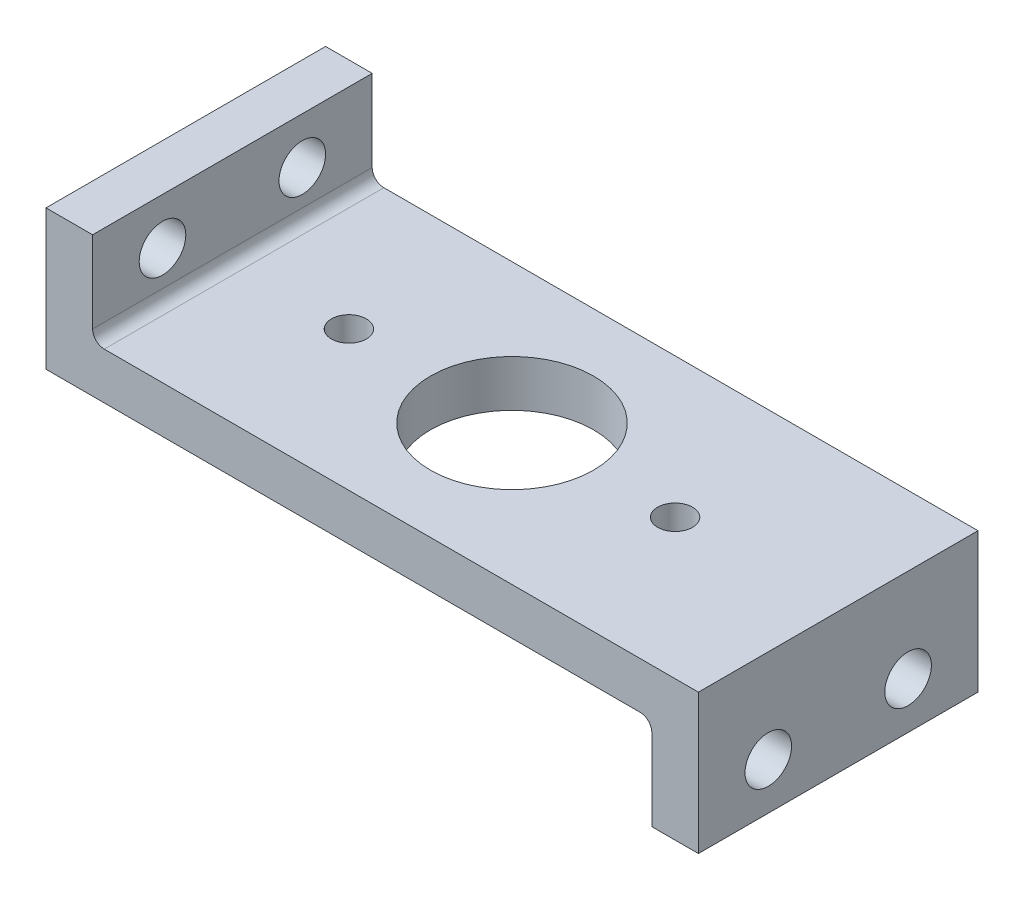
SolidWorks part; units mm, degrees
material "Alloy Steel"
ref_plane "Front Plane" through (0, 0, 0) normal (0, 0, 1) x (1, 0, 0)
ref_plane "Top Plane" through (0, 0, 0) normal (0, 1, 0) x (1, 0, 0)
ref_plane "Right Plane" through (0, 0, 0) normal (1, 0, 0) x (0, 0, -1)
sketch "Sketch1" plane through (0, 0, 0) normal (0, 1, 0) x (1, 0, 0)
  line L1 (-88.9, 38.1) -> (88.9, 38.1)
  line L2 (-88.9, 38.1) -> (-88.9, -38.1)
  line L3 (-88.9, -38.1) -> (88.9, -38.1)
  line L4 (88.9, 38.1) -> (88.9, -38.1)
  circle A0 centre (0, 0) radius 22.225
  circle A1 centre (-44.45, 0) radius 4.7625
  circle A2 centre (44.45, 0) radius 4.7625
  point P4 (0, -38.1)
  point P6 (-88.9, 0)
  dimension "D3" = 44.45
  dimension "D4" = 9.525
  dimension "D5" = 9.525
  dimension "D1" = 177.8
  dimension "D2" = 76.2
  dimension "D6" = 44.45
  dimension "D7" = 88.9
extrude "Boss-Extrude1" add sketch "Sketch1" along normal blind 12.7
sketch "Sketch2" plane through (0, 12.7, 0) normal (0, 1, 0) x (1, 0, 0)
  line L0 (-88.9, -38.1) -> (88.9, -38.1) construction
  line L1 (-88.9, 38.1) -> (-76.2, 38.1)
  line L2 (-88.9, 38.1) -> (-88.9, -38.1)
  line L3 (-88.9, -38.1) -> (-76.2, -38.1)
  line L4 (-76.2, 38.1) -> (-76.2, -38.1)
  dimension "D1" = 12.7
extrude "Boss-Extrude2" add sketch "Sketch2" along normal blind 25.4
sketch "Sketch3" plane through (0, 0, 0) normal (0, -1, 0) x (1, 0, 0)
  line L0 (88.9, -38.1) -> (-88.9, -38.1) construction
  line L1 (88.9, 38.1) -> (76.2, 38.1)
  line L2 (88.9, 38.1) -> (88.9, -38.1)
  line L3 (88.9, -38.1) -> (76.2, -38.1)
  line L4 (76.2, 38.1) -> (76.2, -38.1)
  dimension "D1" = 12.7
extrude "Boss-Extrude3" add sketch "Sketch3" along normal blind 25.4
sketch "Sketch4" plane through (-76.2, 0, 0) normal (1, 0, 0) x (0, 0, -1)
  line L0 (-38.1, 38.1) -> (-38.1, 12.7) construction
  line L1 (38.1, 38.1) -> (38.1, 12.7) construction
  line L2 (38.1, 12.7) -> (38.1, -25.4) construction
  line L3 (-38.1, 12.7) -> (-38.1, -25.4) construction
  line L4 (-38.1, 38.1) -> (38.1, 38.1) construction
  line L5 (38.1, -25.4) -> (-38.1, -25.4) construction
  circle A0 centre (-19.05, 25.4) radius 6.35
  circle A1 centre (19.05, 25.4) radius 6.35
  circle A2 centre (-19.05, -12.7) radius 6.35
  circle A3 centre (19.05, -12.7) radius 6.35
  dimension "D1" = 12.7
  dimension "D2" = 12.7
  dimension "D3" = 12.7
  dimension "D4" = 12.7
  dimension "D5" = 19.05
  dimension "D6" = 19.05
  dimension "D7" = 19.05
  dimension "D8" = 19.05
  dimension "D9" = 12.7
  dimension "D10" = 12.7
  dimension "D11" = 12.7
  dimension "D12" = 12.7
extrude "Cut-Extrude1" cut sketch "Sketch4" against normal through all both and the other way through all
fillet "Fillet1" radius 3.175 2 edges at (76.2, 0, 0) (-76.2, 12.7, 0)
